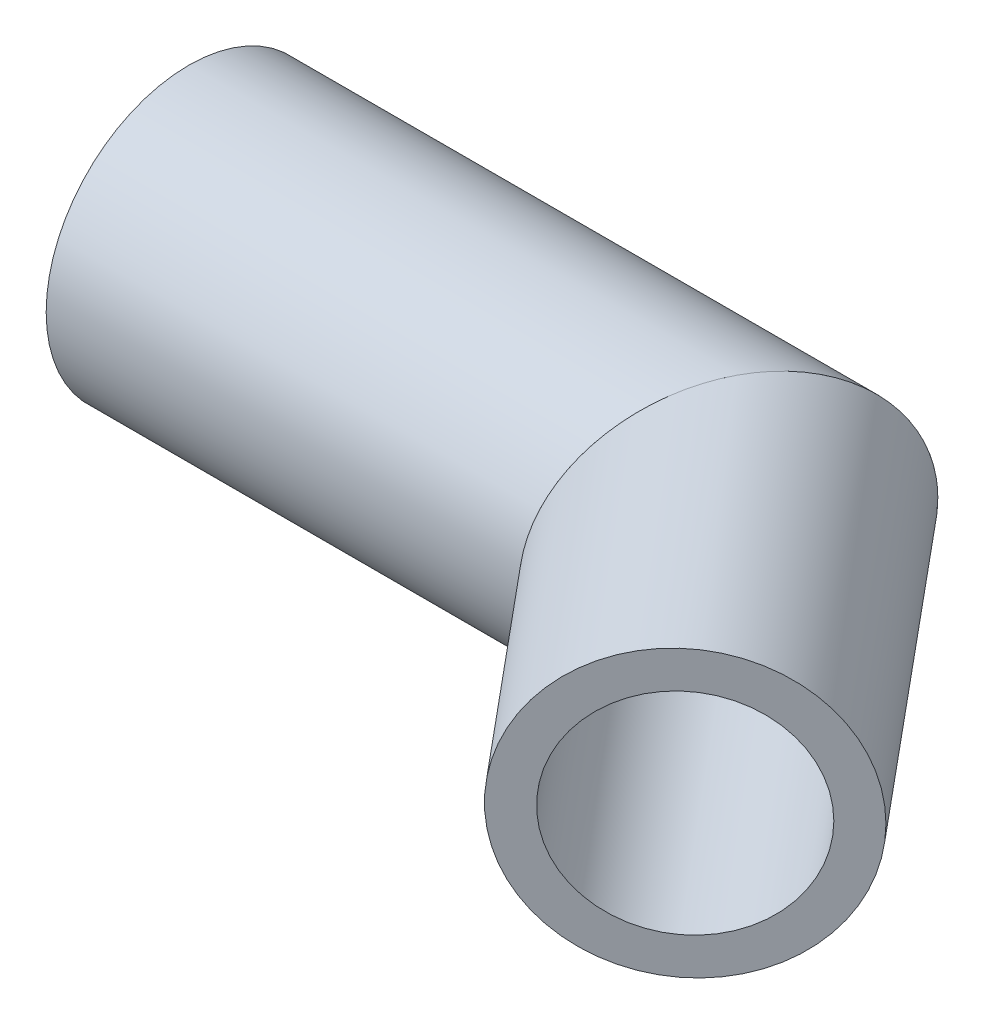
SolidWorks part; units mm, degrees
ref_plane "Front Plane" through (0, 0, 0) normal (0, 0, 1) x (1, 0, 0)
ref_plane "Top Plane" through (0, 0, 0) normal (0, 1, 0) x (1, 0, 0)
ref_plane "Right Plane" through (0, 0, 0) normal (1, 0, 0) x (0, 0, -1)
sketch "Sketch1" plane through (0, 0, 0) normal (0, 1, 0) x (1, 0, 0)
  line L0 (0, 0) -> (40.389, 0)
  line L1 (40.389, 0) -> (56.375, -19.221)
  dimension "D1" = 25
  dimension "D2" = 40.389
  dimension "D3" = 129.75
other "Pipe 0.5 SCH 40(1)"
ref_plane "Plane1" through (0, 0, 0) normal (1, 0, 0) x (0, 0, -1)
sketch "Sketch11" plane through (0, 0, 0) normal (1, 0, 0) x (0, 0, -1)
  circle A0 centre (0, 0) radius 7.8994
  circle A1 centre (0, 0) radius 10.668
  circle A2 centre (0, 0) radius 6.35 construction
  point P5 (0, 10.668)
  point P6 (0, -10.668)
  point P7 (-10.668, 0)
  point P8 (10.668, 0)
  point P9 (0, 0)
  dimension "In_dia" = 15.7988
  dimension "Out_dia" = 21.336
  dimension "D1" = 12.7
sketch "Sketch12" plane through (0, 0, 0) normal (-1, 0, 0) x (0, 0, 1)
  line L0 (0, 0) -> (0, -10.668)
